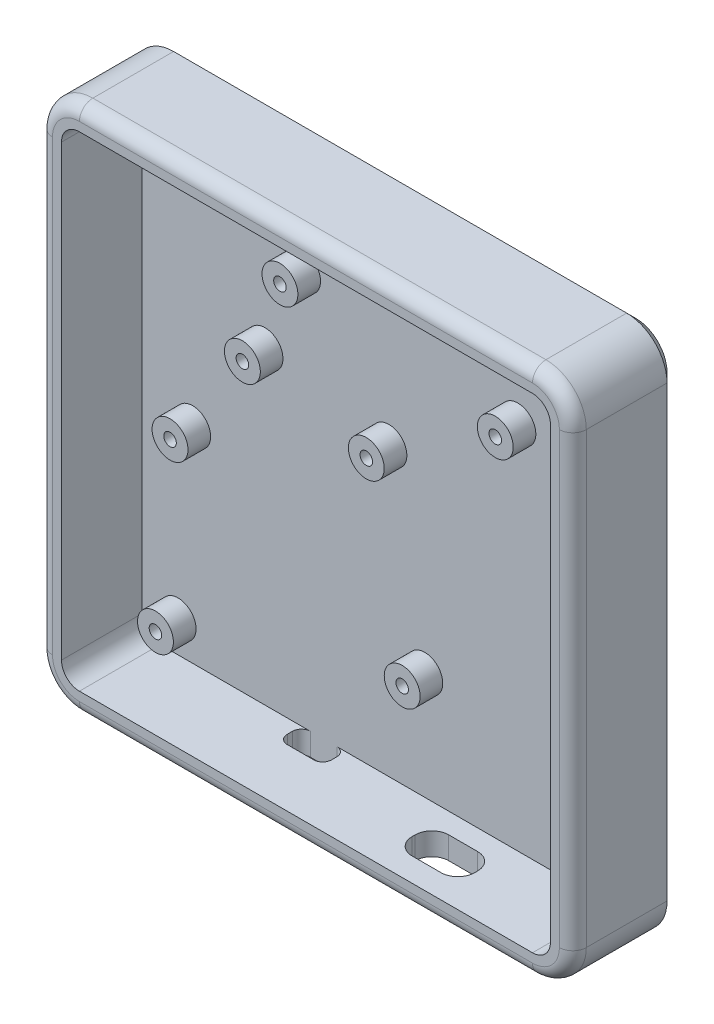
SolidWorks part; units mm, degrees
ref_plane "Front Plane" through (0, 0, 0) normal (0, 0, 1) x (1, 0, 0)
ref_plane "Top Plane" through (0, 0, 0) normal (0, 1, 0) x (1, 0, 0)
ref_plane "Right Plane" through (0, 0, 0) normal (1, 0, 0) x (0, 0, -1)
sketch "Sketch1" plane through (0, 0, 0) normal (0, 0, 1) x (1, 0, 0)
  line L8 (28.6312, 52.5) -> (28.6312, -47.5)
  line L9 (28.6312, 52.5) -> (28.6312, -47.5)
  line L10 (32.6312, -51.5) -> (133.6312, -51.5)
  line L12 (23.6312, 52.5) -> (23.6312, -47.5)
  line L13 (23.6312, 52.5) -> (23.6312, -47.5)
  line L14 (32.6312, -51.5) -> (133.6312, -51.5)
  line L16 (137.6312, -47.5) -> (137.6312, 52.5)
  line L17 (32.6312, -56.5) -> (133.6312, -56.5)
  line L19 (137.6312, -47.5) -> (137.6312, 52.5)
  line L20 (133.6312, 56.5) -> (32.6312, 56.5)
  line L21 (133.6312, 56.5) -> (32.6312, 56.5)
  line L33 (32.6312, -56.5) -> (133.6312, -56.5)
  line L34 (142.6312, -47.5) -> (142.6312, 52.5)
  line L35 (142.6312, -47.5) -> (142.6312, 52.5)
  line L36 (133.6312, 61.5) -> (32.6312, 61.5)
  line L37 (133.6312, 61.5) -> (32.6312, 61.5)
  arc A8 (28.6312, -47.5) -> (32.6312, -51.5) centre (32.6312, -47.5) ccw
  arc A9 (28.6312, -47.5) -> (32.6312, -51.5) centre (32.6312, -47.5) ccw
  arc A10 (133.6312, -51.5) -> (137.6312, -47.5) centre (133.6312, -47.5) ccw
  arc A11 (133.6312, -51.5) -> (137.6312, -47.5) centre (133.6312, -47.5) ccw
  arc A12 (137.6312, 52.5) -> (133.6312, 56.5) centre (133.6312, 52.5) ccw
  arc A13 (137.6312, 52.5) -> (133.6312, 56.5) centre (133.6312, 52.5) ccw
  arc A14 (32.6312, 56.5) -> (28.6312, 52.5) centre (32.6312, 52.5) ccw
  arc A15 (32.6312, 56.5) -> (28.6312, 52.5) centre (32.6312, 52.5) ccw
  arc A16 (23.6312, -47.5) -> (32.6312, -56.5) centre (32.6312, -47.5) ccw
  arc A17 (23.6312, -47.5) -> (32.6312, -56.5) centre (32.6312, -47.5) ccw
  arc A18 (133.6312, -56.5) -> (142.6312, -47.5) centre (133.6312, -47.5) ccw
  arc A19 (133.6312, -56.5) -> (142.6312, -47.5) centre (133.6312, -47.5) ccw
  arc A20 (142.6312, 52.5) -> (133.6312, 61.5) centre (133.6312, 52.5) ccw
  arc A21 (142.6312, 52.5) -> (133.6312, 61.5) centre (133.6312, 52.5) ccw
  arc A22 (32.6312, 61.5) -> (23.6312, 52.5) centre (32.6312, 52.5) ccw
  arc A23 (32.6312, 61.5) -> (23.6312, 52.5) centre (32.6312, 52.5) ccw
  dimension "D1" = 0
  dimension "D2" = 5
extrude "Boss-Extrude1" add sketch "Sketch1" against normal blind 18
sketch "Sketch2" plane through (0, 0, -18) normal (0, 0, -1) x (-1, 0, 0)
  circle A2 centre (-112.3812, 31) radius 4
  circle A3 centre (-64.3812, 36.5) radius 4
  circle A4 centre (-56.0062, 17.375) radius 4
  circle A5 centre (-83.6312, 12.5) radius 4
  circle A6 centre (-39.8812, -5.75) radius 4
  circle A7 centre (-36.6312, -44.5) radius 4
  circle A8 centre (-130.6312, -44.5) radius 4
  circle A9 centre (-91.6312, -27.5) radius 4
extrude "Boss-Extrude2" add sketch "Sketch2" against normal up to surface (5.0446 mm away) separate body
sketch "Sketch6" plane through (0, 0, -18) normal (0, 0, -1) x (-1, 0, 0)
  line L4 (-32.6312, 61.5) -> (-133.6312, 61.5)
  line L6 (-23.6312, -47.5) -> (-23.6312, 52.5)
  line L7 (-23.6312, -47.5) -> (-23.6312, 52.5)
  line L8 (-32.6312, 61.5) -> (-133.6312, 61.5)
  line L9 (-142.6312, 52.5) -> (-142.6312, -47.5)
  line L10 (-142.6312, 52.5) -> (-142.6312, -47.5)
  line L11 (-133.6312, -56.5) -> (-32.6312, -56.5)
  line L12 (-133.6312, -56.5) -> (-32.6312, -56.5)
  arc A4 (-32.6312, -56.5) -> (-23.6312, -47.5) centre (-32.6312, -47.5) ccw
  arc A5 (-32.6312, -56.5) -> (-23.6312, -47.5) centre (-32.6312, -47.5) ccw
  arc A6 (-23.6312, 52.5) -> (-32.6312, 61.5) centre (-32.6312, 52.5) ccw
  arc A7 (-23.6312, 52.5) -> (-32.6312, 61.5) centre (-32.6312, 52.5) ccw
  arc A8 (-133.6312, 61.5) -> (-142.6312, 52.5) centre (-133.6312, 52.5) ccw
  arc A9 (-133.6312, 61.5) -> (-142.6312, 52.5) centre (-133.6312, 52.5) ccw
  arc A10 (-142.6312, -47.5) -> (-133.6312, -56.5) centre (-133.6312, -47.5) ccw
  arc A11 (-142.6312, -47.5) -> (-133.6312, -56.5) centre (-133.6312, -47.5) ccw
  dimension "D1" = 0
extrude "Boss-Extrude4" add sketch "Sketch6" along normal blind 5
chamfer "Chamfer1" distance 2 angle 45 8 edges at (23.6312, 2.5, -23) (83.1312, -56.5, -23) (139.9952, -53.864, -23) (142.6312, 2.5, -23) (139.9952, 58.864, -23) (83.1312, 61.5, -23) (26.2672, 58.864, -23) (26.2672, -53.864, -23)
sketch "Sketch8" plane through (0, -56.5, 0) normal (0, 1, 0) x (1, 0, 0)
  line L0 (101.5362, 5.27) -> (107.9762, 5.27)
  line L1 (111.7262, 9.02) -> (111.7262, 9.68)
  line L2 (107.9762, 13.43) -> (104.478, 13.43)
  line L3 (104.478, 13.43) -> (104.478, 13.43)
  line L4 (104.478, 13.43) -> (104.478, 13.43)
  line L5 (104.478, 13.43) -> (104.478, 13.43)
  line L6 (104.478, 13.43) -> (104.478, 13.43)
  line L7 (104.478, 13.43) -> (104.478, 13.43)
  line L8 (104.478, 13.43) -> (104.478, 13.43)
  line L9 (104.478, 13.43) -> (104.478, 13.43)
  line L18 (104.478, 13.43) -> (101.5362, 13.43)
  line L19 (97.7862, 9.68) -> (97.7862, 9.02)
  line L20 (101.5362, 7.77) -> (107.9762, 7.77)
  line L21 (100.2862, 9.68) -> (100.2862, 9.02)
  line L22 (104.468, 10.93) -> (101.5362, 10.93)
  line L23 (104.468, 10.73) -> (104.468, 10.93)
  line L24 (101.5362, 10.73) -> (104.468, 10.73)
  line L25 (100.4862, 9.02) -> (100.4862, 9.68)
  line L26 (107.9762, 7.97) -> (101.5362, 7.97)
  line L27 (109.0262, 9.68) -> (109.0262, 9.02)
  line L28 (104.488, 10.73) -> (107.9762, 10.73)
  line L29 (104.488, 10.93) -> (104.488, 10.73)
  line L30 (107.9762, 10.93) -> (104.488, 10.93)
  line L31 (109.2262, 9.02) -> (109.2262, 9.68)
  line L32 (101.5362, 7.77) -> (107.9762, 7.77)
  line L33 (100.2862, 9.68) -> (100.2862, 9.02)
  line L34 (104.468, 10.93) -> (101.5362, 10.93)
  line L35 (104.468, 10.73) -> (104.468, 10.93)
  line L36 (101.5362, 10.73) -> (104.468, 10.73)
  line L37 (100.4862, 9.02) -> (100.4862, 9.68)
  line L38 (107.9762, 7.97) -> (101.5362, 7.97)
  line L39 (109.0262, 9.68) -> (109.0262, 9.02)
  line L40 (104.488, 10.73) -> (107.9762, 10.73)
  line L41 (104.488, 10.93) -> (104.488, 10.73)
  line L42 (107.9762, 10.93) -> (104.488, 10.93)
  line L43 (109.2262, 9.02) -> (109.2262, 9.68)
  line L44 (72, 12.8557) -> (66.1152, 12.8557)
  line L45 (64.1152, 14.8557) -> (64.1152, 16)
  line L46 (66.1152, 18) -> (72, 18)
  line L47 (74, 16) -> (74, 14.8557)
  arc A0 (100.2862, 9.02) -> (101.5362, 7.77) centre (101.5362, 9.02) ccw
  arc A1 (101.5362, 10.93) -> (100.2862, 9.68) centre (101.5362, 9.68) ccw
  arc A2 (101.5362, 10.73) -> (100.4862, 9.68) centre (101.5362, 9.68) ccw
  arc A3 (100.4862, 9.02) -> (101.5362, 7.97) centre (101.5362, 9.02) ccw
  arc A4 (107.9762, 7.97) -> (109.0262, 9.02) centre (107.9762, 9.02) ccw
  arc A5 (109.0262, 9.68) -> (107.9762, 10.73) centre (107.9762, 9.68) ccw
  arc A6 (109.2262, 9.68) -> (107.9762, 10.93) centre (107.9762, 9.68) ccw
  arc A7 (107.9762, 7.77) -> (109.2262, 9.02) centre (107.9762, 9.02) ccw
  arc A8 (100.2862, 9.02) -> (101.5362, 7.77) centre (101.5362, 9.02) ccw
  arc A9 (101.5362, 10.93) -> (100.2862, 9.68) centre (101.5362, 9.68) ccw
  arc A10 (101.5362, 10.73) -> (100.4862, 9.68) centre (101.5362, 9.68) ccw
  arc A11 (100.4862, 9.02) -> (101.5362, 7.97) centre (101.5362, 9.02) ccw
  arc A12 (107.9762, 7.97) -> (109.0262, 9.02) centre (107.9762, 9.02) ccw
  arc A13 (109.0262, 9.68) -> (107.9762, 10.73) centre (107.9762, 9.68) ccw
  arc A14 (109.2262, 9.68) -> (107.9762, 10.93) centre (107.9762, 9.68) ccw
  arc A15 (107.9762, 7.77) -> (109.2262, 9.02) centre (107.9762, 9.02) ccw
  arc A16 (107.9762, 5.27) -> (111.7262, 9.02) centre (107.9762, 9.02) ccw
  arc A17 (111.7262, 9.68) -> (107.9762, 13.43) centre (107.9762, 9.68) ccw
  arc A18 (104.478, 13.43) -> (104.478, 13.43) centre (104.478, 13.43) ccw
  arc A19 (104.478, 13.43) -> (104.478, 13.43) centre (104.478, 13.43) ccw
  arc A20 (104.478, 13.43) -> (104.478, 13.43) centre (104.478, 13.43) ccw
  arc A21 (104.478, 13.43) -> (104.478, 13.43) centre (104.478, 13.43) ccw
  arc A22 (101.5362, 13.43) -> (97.7862, 9.68) centre (101.5362, 9.68) ccw
  arc A23 (97.7862, 9.02) -> (101.5362, 5.27) centre (101.5362, 9.02) ccw
  arc A24 (64.1152, 16) -> (66.1152, 18) centre (66.1152, 16) cw
  arc A25 (74, 16) -> (72, 18) centre (72, 16) ccw
  arc A26 (74, 14.8557) -> (72, 12.8557) centre (72, 14.8557) cw
  arc A27 (66.1152, 12.8557) -> (64.1152, 14.8557) centre (66.1152, 14.8557) cw
  dimension "D3" = 2
  dimension "D1" = 0
  dimension "D2" = 2.5
extrude "Cut-Extrude4" cut sketch "Sketch8" along normal blind 10 contours A23 L19 A22 L18 L2 A17 L1 A16 L0 L32 A15 L43 A14 L42 L41 L40 A13 L39 A12 L38 A11 L37 A10 L36 L35 L34 A9 L33 A8 | A15 L32 A8 L33 A9 L34 L35 L36 A10 L37 A11 L38 A12 L39 A13 L40 L41 L42 A14 L43 | L44 A27 L45 A24 L46 A25 L47 A26
sketch "Sketch9" plane through (0, 0, -12.9554) normal (0, 0, 1) x (1, 0, 0)
  circle A0 centre (130.6312, -44.5) radius 1.4
  circle A1 centre (36.6312, -44.5) radius 1.4
  circle A2 centre (91.6312, -27.5) radius 1.4
  circle A3 centre (83.6312, 12.5) radius 1.4
  circle A4 centre (56.0062, 17.375) radius 1.4
  circle A5 centre (39.8812, -5.75) radius 1.4
  circle A6 centre (112.3812, 31) radius 1.4
  circle A7 centre (64.3812, 36.5) radius 1.4
extrude "Cut-Extrude5" cut sketch "Sketch9" against normal up to surface (5.0446 mm away)
fillet "Fillet1" radius 3 8 edges at (139.9952, -53.864, 0) (83.1312, -56.5, 0) (26.2672, -53.864, 0) (23.6312, 2.5, 0) (26.2672, 58.864, 0) (83.1312, 61.5, 0) (139.9952, 58.864, 0) (142.6312, 2.5, 0)
